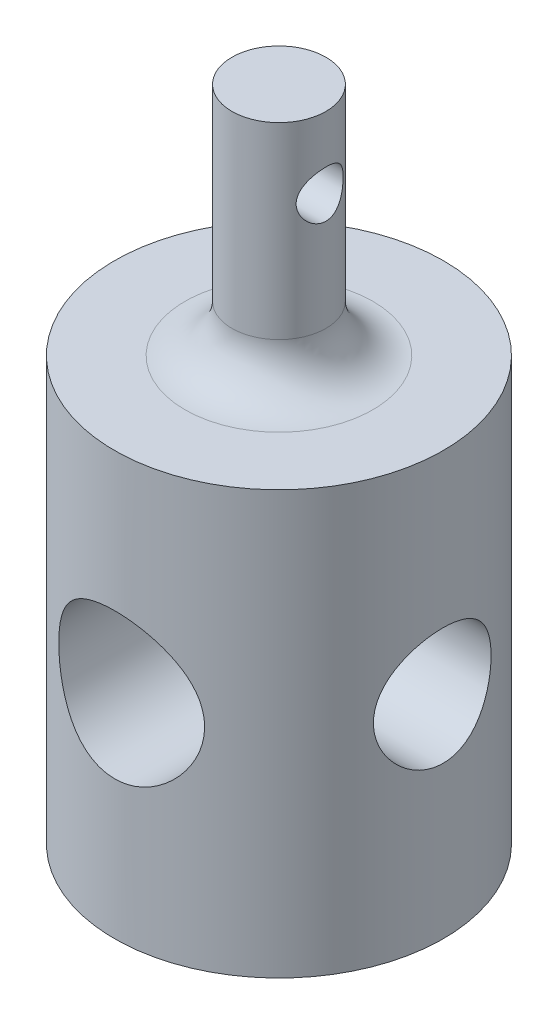
SolidWorks part; units mm, degrees
ref_plane "Front Plane" through (0, 0, 0) normal (0, 0, 1) x (1, 0, 0)
ref_plane "Top Plane" through (0, 0, 0) normal (0, 1, 0) x (1, 0, 0)
ref_plane "Right Plane" through (0, 0, 0) normal (1, 0, 0) x (0, 0, -1)
sketch "Sketch1" plane through (0, 0, 0) normal (0, 1, 0) x (1, 0, 0)
  circle A0 centre (0, 0) radius 1
  dimension "D1" = 2
extrude "Boss-Extrude1" add sketch "Sketch1" along normal blind 5
sketch "Sketch2" plane through (0, 0, 0) normal (0, -1, 0) x (1, 0, 0)
  circle A0 centre (0, 0) radius 3.5
  dimension "D1" = 7
extrude "Boss-Extrude2" add sketch "Sketch2" along normal blind 9
hole_wizard "Ø3.0mm Dowel Hole1" positions "3DSketch1" profile "Sketch3" hole size "Ø3.0" standard "ANSI Metric" end condition through all
sketch3d "3DSketch1"
  line L0 (0, 0, 0) -> (0, -9, 0) construction
  line L1 (0, -9, 0) -> (0, 0, 0) construction
  line L4 (0, -4.5, 0) -> (2.4963, -4.5, 0) construction
  line L6 (0, -4.5, 0) -> (-2.4854, -4.5, 0) construction
  point P0 (0.0044, -4.5009, 3.5)
  point P26 (0, -4.5, 0)
sketch "Sketch3" plane through (0.0044, -4.5009, 3.5) normal (0, 1, 0) x (1, 0, -0.0013)
  line L0 (0, 0) -> (0, 7.0044)
  line L1 (0, 7.0044) -> (1.55, 7.0044)
  line L2 (1.55, 7.0044) -> (1.55, 0)
  line L5 (1.55, 0) -> (0, 0)
  line L11 (0, -6.35) -> (0, 107.95) construction
  dimension "Thru Hole Dia." = 3.1
  dimension "Thru Hole Depth" = 7.0044
hole_wizard "Ø3.0mm Dowel Hole2" positions "3DSketch2" profile "Sketch4" hole size "Ø3.0" standard "ANSI Metric"
sketch3d "3DSketch2"
  point P0 (3.5, -4.514, 0.007)
  point P10 (3.4999, -4.5655, 0.0273)
  point P11 (0, 0, 0)
  point P12 (0, 0, 0)
  point P13 (3.4937, -4.5449, -0.2094)
  point P14 (0, -4.514, 0)
sketch "Sketch4" plane through (3.5, -4.514, 0.007) normal (0, 1, 0) x (0.002, 0, -1)
  line L0 (0, 0) -> (0, 3.7511)
  line L1 (0, 3.7511) -> (1.25, 3)
  line L2 (1.25, 3) -> (1.25, 0)
  line L5 (1.25, 0) -> (0, 0)
  line L10 (0, 3.7511) -> (-1.25, 3) construction
  line L11 (0, -6.35) -> (0, 107.95) construction
  dimension "Hole Dia." = 2.5
  dimension "Hole Depth" = 3
  dimension "Drill Angle" = 118
hole_wizard "Ø1.0mm Dowel Hole1" positions "3DSketch3" profile "Sketch5" hole size "Ø1.0" standard "ANSI Metric" end condition through all
sketch3d "3DSketch3"
  point P0 (1, 3.4761, 0)
sketch "Sketch5" plane through (1, 3.4761, 0) normal (0, 1, 0) x (0, 0, -1)
  line L0 (0, 0) -> (0, 4.5)
  line L1 (0, 4.5) -> (0.5, 4.5)
  line L2 (0.5, 4.5) -> (0.5, 0)
  line L5 (0.5, 0) -> (0, 0)
  line L11 (0, -6.35) -> (0, 107.95) construction
  dimension "Thru Hole Dia." = 1
  dimension "Thru Hole Depth" = 4.5
fillet "Fillet1" radius 1 1 edges at (0, 0, 1)
